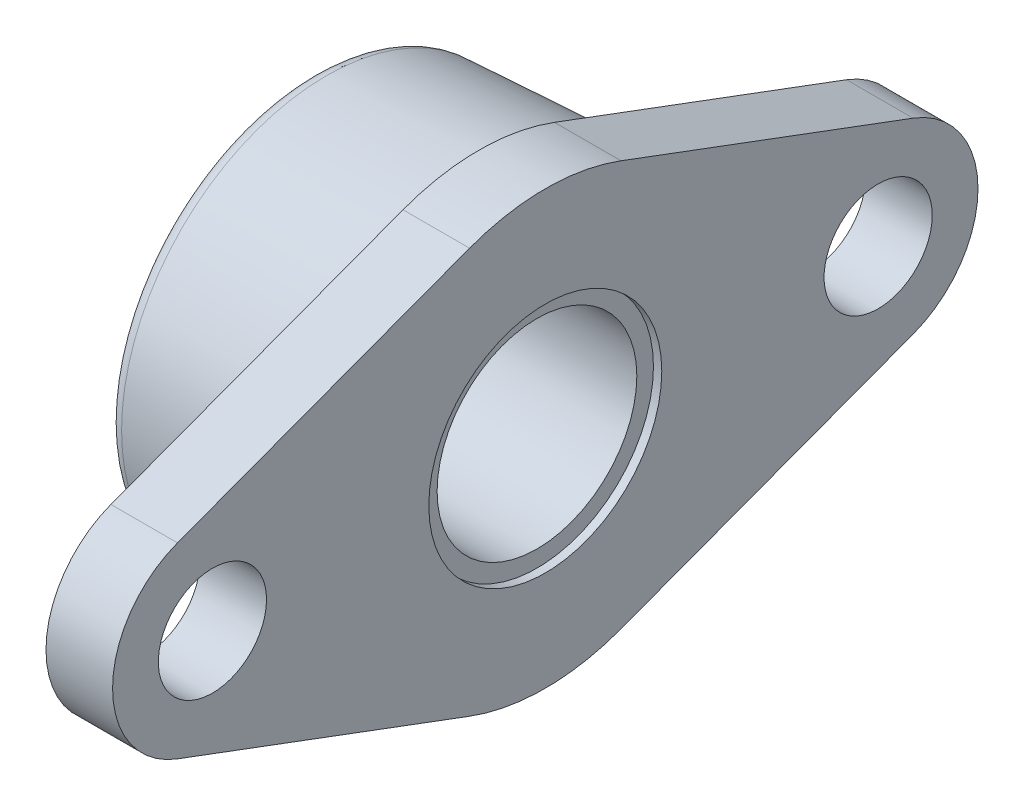
SolidWorks part; units mm, degrees
ref_plane "Front" through (0, 0, 0) normal (0, 0, 1) x (1, 0, 0)
ref_plane "Top" through (0, 0, 0) normal (0, 1, 0) x (1, 0, 0)
ref_plane "Side" through (0, 0, 0) normal (1, 0, 0) x (0, 0, -1)
sketch "Sketch1" plane through (0, 0, 0) normal (1, 0, 0) x (0, 0, -1)
  line L0 (31.6416, 0) -> (-33.1843, 0) construction
  line L1 (0, 16.6193) -> (0, -17.6431) construction
  line L8 (-7.2231, -19.3322) -> (-35.0837, -8.9225)
  line L9 (7.2231, -19.3322) -> (35.0837, -8.9225)
  line L10 (35.0838, 8.9225) -> (7.2231, 19.3322)
  line L11 (-7.2231, 19.3322) -> (-35.0838, 8.9225)
  circle A0 centre (-31.75, 0) radius 5.1594
  circle A1 centre (31.75, 0) radius 5.1594
  arc A2 (-35.0838, 8.9225) -> (-35.0837, -8.9225) centre (-31.75, 0) ccw
  arc A3 (35.0837, -8.9225) -> (35.0838, 8.9225) centre (31.75, 0) ccw
  arc A4 (-7.2231, -19.3322) -> (7.2231, -19.3322) centre (0, 0) ccw
  arc A5 (7.2231, 19.3322) -> (-7.2231, 19.3322) centre (0, 0) ccw
  dimension "Dim F" = 10.3187
  dimension "Dim C" = 41.275
  dimension "Dim B" = 63.5
  dimension "Dim A" = 82.55
extrude "Base-Extrude" add sketch "Sketch1" against normal blind 6.35
sketch "Sketch2" plane through (0, 0, 0) normal (-1, 0, 0) x (0, 0, 1)
  circle A0 centre (0, 0) radius 20.6375
  arc A1 (7.2231, 19.3322) -> (-7.2231, 19.3322) centre (0, 0) ccw construction
extrude "Boss-Extrude1" add sketch "Sketch2" along normal blind 22.225 draft 3
sketch "Sketch3" plane through (-22.225, 0, 0) normal (-1, 0, 0) x (0, 0, 1)
  circle A0 centre (0, 0) radius 9.525
  dimension "Shaft Size" = 19.05
extrude "Cut-Extrude1" cut sketch "Sketch3" against normal through all
sketch "Sketch4" plane through (-22.225, 0, 0) normal (-1, 0, 0) x (0, 0, 1)
  circle A0 centre (0, 0) radius 11.1125
  circle A1 centre (0, 0) radius 9.525 construction
  circle A2 centre (0, 0) radius 9.525
  dimension "Bushing Dia" = 22.225
extrude "Boss-Extrude2" add sketch "Sketch4" along normal blind 0.0254 draft 15
sketch "Sketch5" plane through (0, 0, 0) normal (1, 0, 0) x (0, 0, -1)
  circle A1 centre (0, 0) radius 11.1125 construction
  circle A3 centre (0, 0) radius 11.1125
extrude "Cut-Extrude2" cut sketch "Sketch5" against normal blind 0.7937
fillet "Fillet1" radius 1.4287 1 edges at (-22.225, 0, 19.4727)
